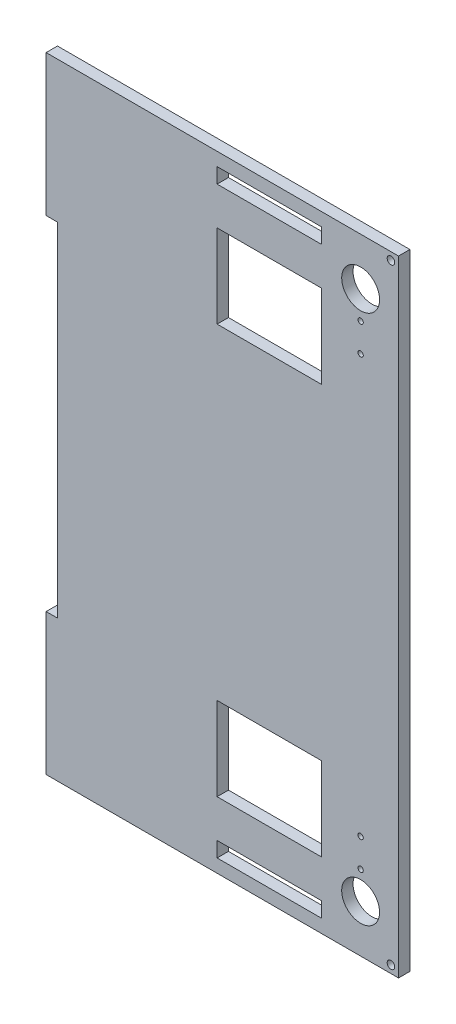
SolidWorks part; units mm, degrees
ref_plane "Plan de face" through (0, 0, 0) normal (0, 0, 1) x (1, 0, 0)
ref_plane "Plan de dessus" through (0, 0, 0) normal (0, 1, 0) x (1, 0, 0)
ref_plane "Plan de droite" through (0, 0, 0) normal (1, 0, 0) x (0, 0, -1)
sketch "Esquisse1" plane through (0, 0, 0) normal (0, 0, 1) x (1, 0, 0)
  line L1 (0, 0) -> (-186, 0)
  line L2 (0, 0) -> (0, 330)
  line L3 (0, 330) -> (-186, 330)
  line L4 (-186, 0) -> (-186, 330)
  dimension "D1" = 330
  dimension "D2" = 186
extrude "Boss.-Extru.1" add sketch "Esquisse1" along normal blind 6
sketch "Esquisse3" plane through (0, 0, 6) normal (0, 0, 1) x (1, 0, 0)
  line L0 (-186, 0) -> (0, 0) construction
  line L1 (-95.75, 15) -> (-40.75, 15)
  line L2 (-95.75, 15) -> (-95.75, 7)
  line L3 (-95.75, 7) -> (-40.75, 7)
  line L4 (-40.75, 15) -> (-40.75, 7)
  line L5 (-95.75, 79) -> (-40.75, 79)
  line L6 (-95.75, 79) -> (-95.75, 35)
  line L7 (-95.75, 35) -> (-40.75, 35)
  line L8 (-40.75, 79) -> (-40.75, 35)
  line L9 (0, 0) -> (0, 330) construction
  line L10 (-273.5222, 165) -> (26.4778, 165) construction
  line L13 (-95.75, 251) -> (-40.75, 251)
  line L14 (-95.75, 251) -> (-95.75, 295)
  line L15 (-95.75, 295) -> (-40.75, 295)
  line L16 (-40.75, 251) -> (-40.75, 295)
  line L17 (-40.75, 315) -> (-40.75, 323)
  line L18 (-95.75, 315) -> (-40.75, 315)
  line L19 (-95.75, 323) -> (-40.75, 323)
  line L20 (-95.75, 315) -> (-95.75, 323)
  circle A0 centre (-4, 4) radius 2
  circle A1 centre (-20, 25) radius 10
  circle A2 centre (-20, 39.73) radius 1.4
  circle A3 centre (-20, 54.73) radius 1.4
  circle A4 centre (-20, 275.27) radius 1.4
  circle A5 centre (-20, 290.27) radius 1.4
  circle A6 centre (-4, 326) radius 2
  circle A7 centre (-20, 305) radius 10
  dimension "D5" = 4
  dimension "D8" = 20
  dimension "D11" = 2.8
  dimension "D12" = 2.8
  dimension "D1" = 55
  dimension "D2" = 20
  dimension "D3" = 7
  dimension "D4" = 55
  dimension "D6" = 4
  dimension "D7" = 4
  dimension "D9" = 25
  dimension "D10" = 20
  dimension "D13" = 14.73
  dimension "D14" = 20
  dimension "D15" = 15
  dimension "D16" = 20
  dimension "D17" = 8
  dimension "D18" = 44
  dimension "D19" = 86
  dimension "D20" = 40.75
  dimension "D21" = 40.75
extrude "Enlèv. mat.-Extru.2" cut sketch "Esquisse3" against normal blind 6
sketch "Esquisse4" plane through (0, 0, 0) normal (0, 0, -1) x (-1, 0, 0)
  line L0 (186, 330) -> (186, 0) construction
  line L1 (186, 74.5) -> (180, 74.5)
  line L2 (186, 74.5) -> (186, 255.5)
  line L3 (186, 255.5) -> (180, 255.5)
  line L4 (180, 74.5) -> (180, 255.5)
  line L5 (186, 0) -> (0, 0) construction
  dimension "D1" = 6
  dimension "D2" = 181
  dimension "D3" = 74.5
extrude "Enlèv. mat.-Extru.3" cut sketch "Esquisse4" against normal through all
